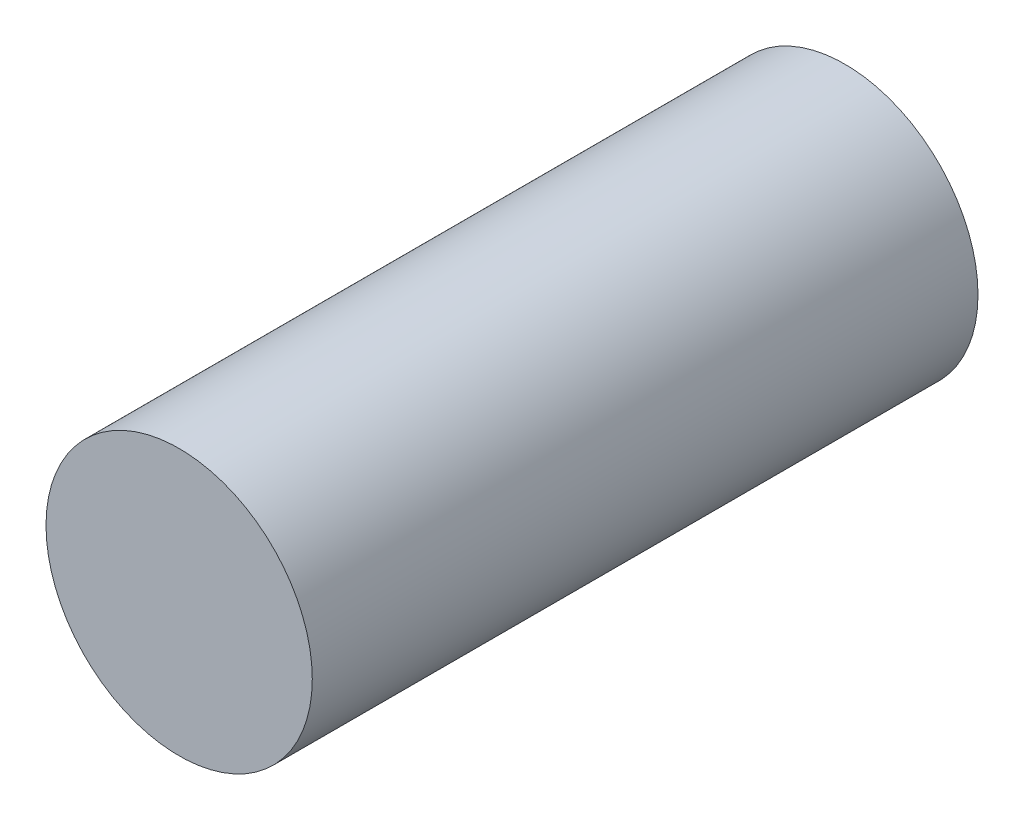
SolidWorks part; units mm, degrees
ref_plane "Front Plane" through (0, 0, 0) normal (0, 0, 1) x (1, 0, 0)
ref_plane "Top Plane" through (0, 0, 0) normal (0, 1, 0) x (1, 0, 0)
ref_plane "Right Plane" through (0, 0, 0) normal (1, 0, 0) x (0, 0, -1)
other "Configuration Table"
sketch "Sketch1" plane through (0, 0, 0) normal (0, 0, 1) x (1, 0, 0)
  circle A0 centre (460, 924) radius 4
extrude "TOPPING_kat3_kapak_pimi_D8_2" add sketch "Sketch1" against normal blind 20 from offset 40 separate body
